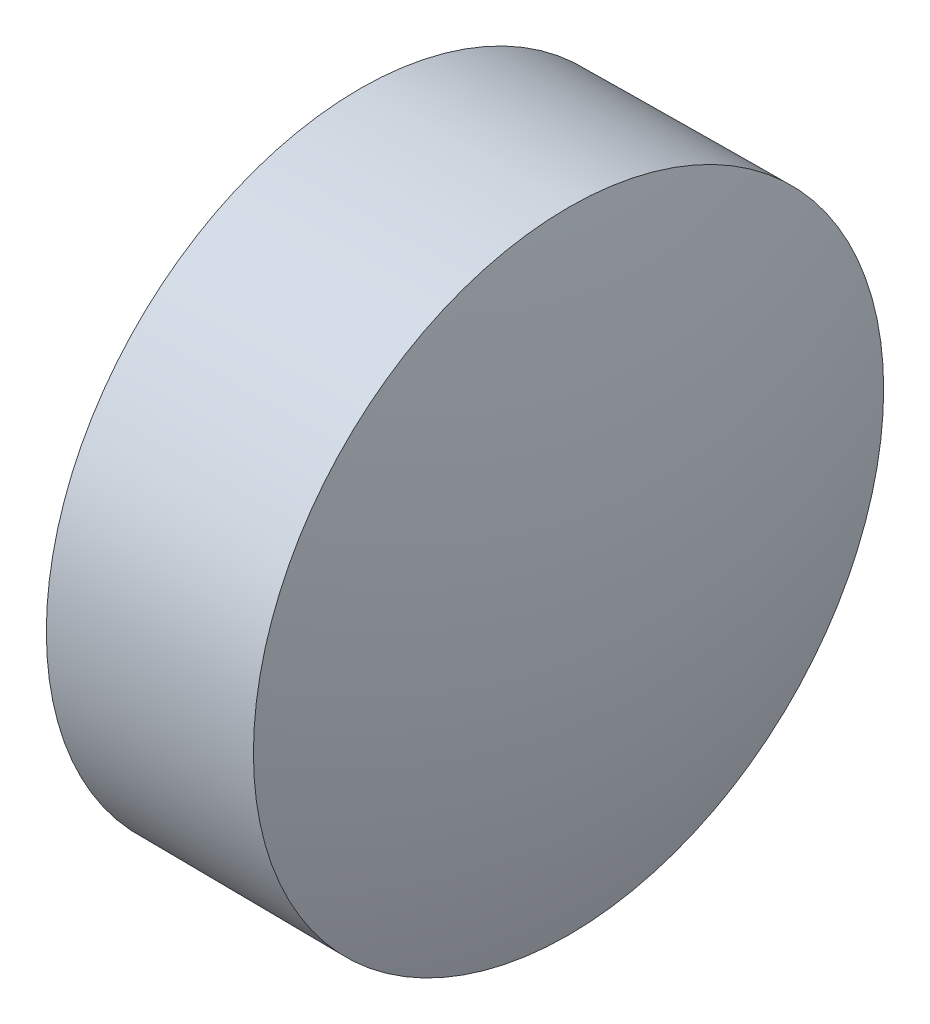
SolidWorks part; units mm, degrees
material "玻璃"
ref_plane "前视基准面" through (0, 0, 0) normal (0, 0, 1) x (1, 0, 0)
ref_plane "上视基准面" through (0, 0, 0) normal (0, 1, 0) x (1, 0, 0)
ref_plane "右视基准面" through (0, 0, 0) normal (1, 0, 0) x (0, 0, -1)
sketch "草图1" plane through (0, 0, 0) normal (0, 0, 1) x (1, 0, 0)
  line L0 (0, 0) -> (0.4133, 0)
  line L1 (0.0055, 0.5001) -> (0.3383, 0.5026)
  arc A0 (0.0055, 0.5001) -> (0, 0) centre (22.6995, 0) ccw
  arc A1 (0.4133, 0) -> (0.3383, 0.5026) centre (-1.3078, 0) ccw
revolve "旋转1" add sketch "草图1" angle 360 about L0
